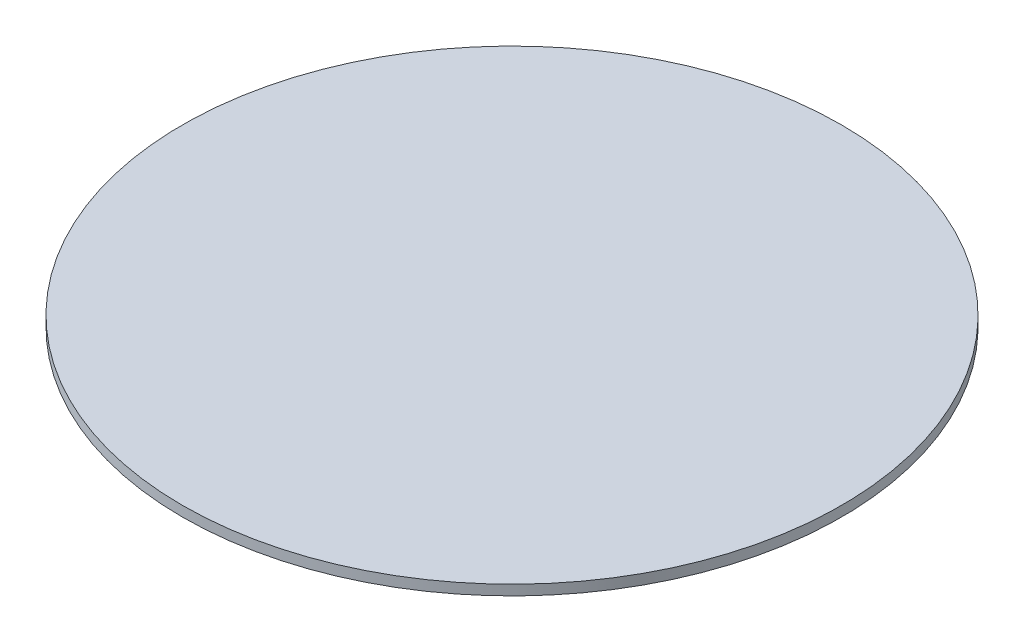
SolidWorks part; units mm, degrees
ref_plane "Front Plane" through (0, 0, 0) normal (0, 0, 1) x (1, 0, 0)
ref_plane "Top Plane" through (0, 0, 0) normal (0, 1, 0) x (1, 0, 0)
ref_plane "Right Plane" through (0, 0, 0) normal (1, 0, 0) x (0, 0, -1)
sketch "Sketch1" plane through (0, 0, 0) normal (0, 1, 0) x (1, 0, 0)
  circle A0 centre (0, 0) radius 51.562
  dimension "D1" = 103.124
extrude "Boss-Extrude1" add sketch "Sketch1" along normal blind 1.59
